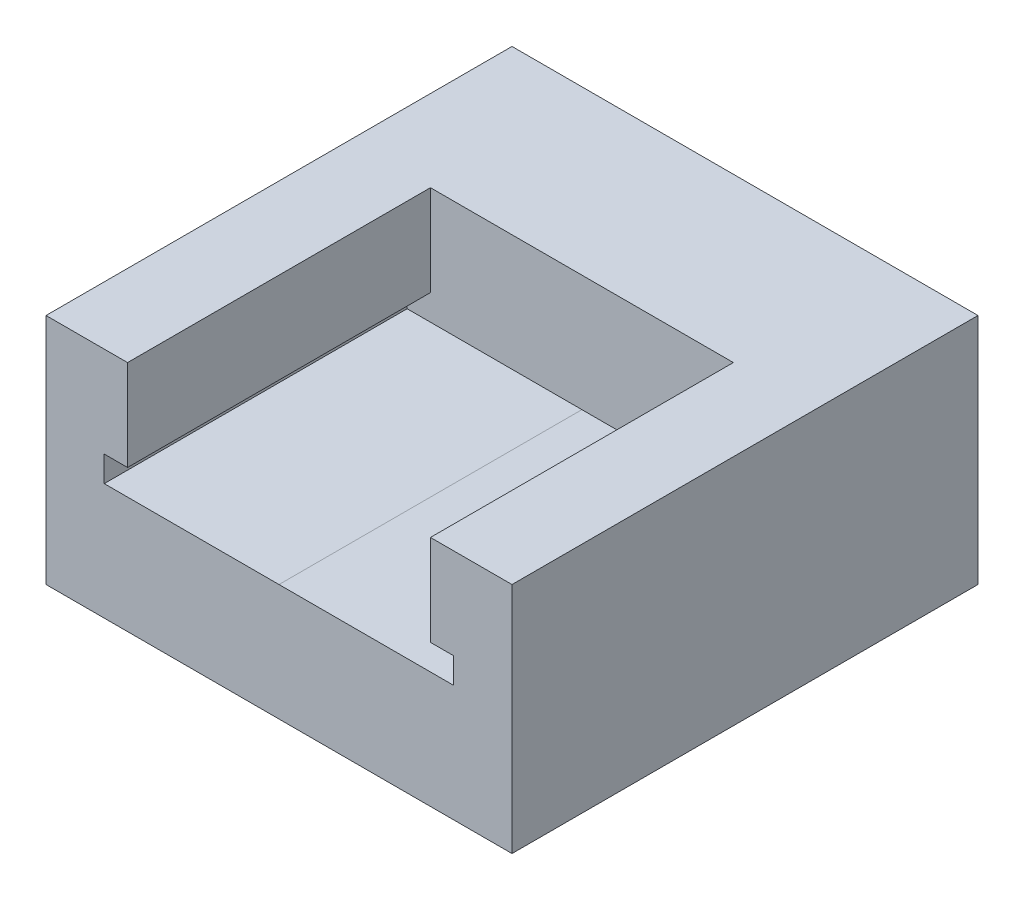
SolidWorks part; units mm, degrees
ref_plane "Front Plane" through (0, 0, 0) normal (0, 0, 1) x (1, 0, 0)
ref_plane "Top Plane" through (0, 0, 0) normal (0, 1, 0) x (1, 0, 0)
ref_plane "Right Plane" through (0, 0, 0) normal (1, 0, 0) x (0, 0, -1)
sketch "Sketch1" plane through (0, 0, 0) normal (0, 0, 1) x (1, 0, 0)
  line L1 (-10, -5) -> (10, -5)
  line L2 (-10, -5) -> (-10, 5)
  line L3 (-10, 5) -> (10, 5)
  line L4 (10, -5) -> (10, 5)
  line L5 (-10, -5) -> (10, 5) construction
  line L6 (-10, 5) -> (10, -5) construction
  point P0 (0, 0)
  dimension "D1" = 10
  dimension "D2" = 20
extrude "Boss-Extrude1" add sketch "Sketch1" along normal blind 20
sketch "Sketch2" plane through (0, 0, 20) normal (0, 0, 1) x (1, 0, 0)
  line L0 (-6.5, 5) -> (-6.5, 1.1)
  line L1 (10, 5) -> (-10, 5) construction
  line L2 (-6.5, 1.1) -> (-7.5, 1.1)
  line L3 (-7.5, 1.1) -> (-7.5, 0)
  line L4 (-7.5, 0) -> (0, 0)
  line L5 (7.5, 0) -> (7.5, 1.1)
  line L6 (7.5, 1.1) -> (6.5, 1.1)
  line L7 (6.5, 1.1) -> (6.5, 5)
  line L8 (0, 0) -> (7.5, 0)
  point P11 (-4.4343, 1.1)
  point P12 (-7.5, 1.1)
  point P13 (-3.9702, 1.1)
  dimension "D1" = 15
  dimension "D2" = 1.1
  dimension "D3" = 13
extrude "Cut-Extrude1" cut sketch "Sketch2" against normal blind 13 and the other way through all
